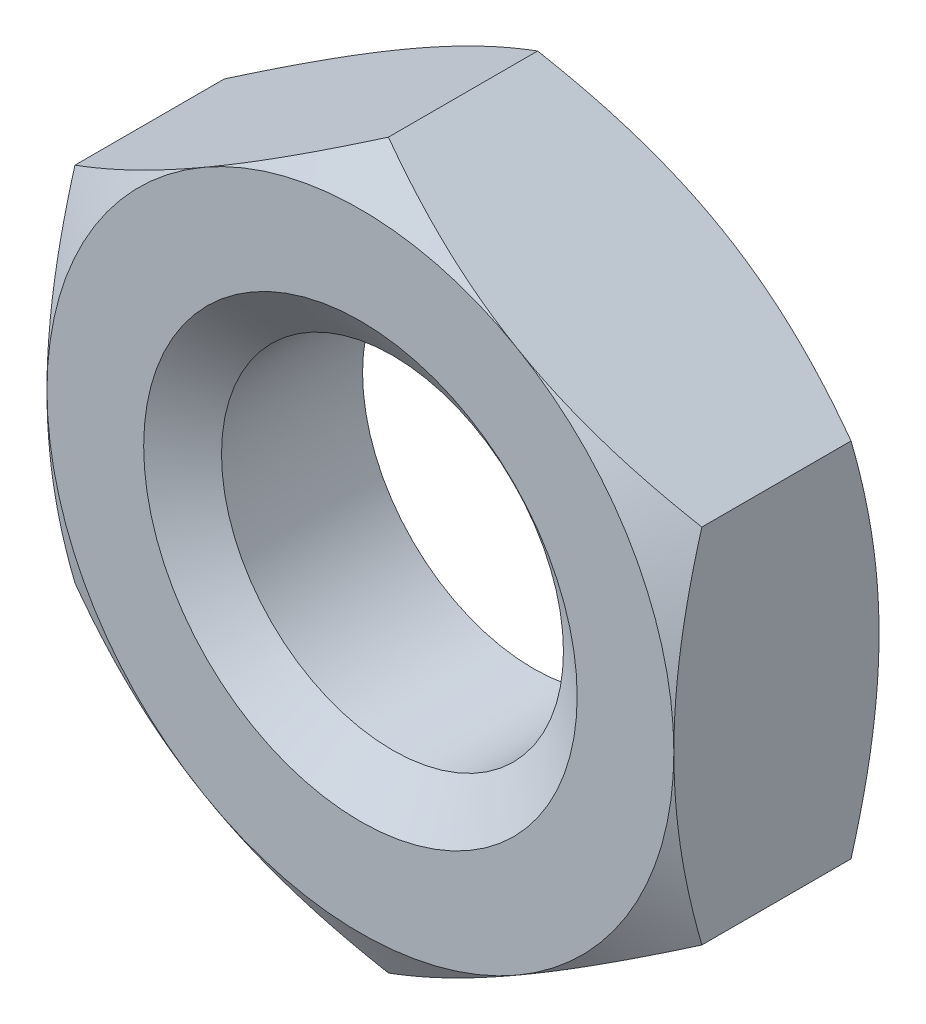
SolidWorks part; units mm, degrees
extrude "BaseNut" add sketch "BaseNutSke" against normal blind 1.8
sketch "BaseNutSke" plane through (0, 0, 0) normal (0, 0, 1) x (1, 0, 0)
  line L6 (2.75, 1.5877) -> (2.75, -1.5877)
  line L7 (-2.75, 1.5877) -> (-2.75, -1.5877)
  line L8 (2.75, 1.5877) -> (0, 3.1754)
  line L9 (0, 3.1754) -> (-2.75, 1.5877)
  line L10 (-2.75, -1.5877) -> (0, -3.1754)
  line L11 (0, -3.1754) -> (2.75, -1.5877)
  circle A0 centre (0, 0) radius 1.5
  point P8 (-2.75, 0)
  point P9 (0, 1.5)
  point P13 (0, 0)
  dimension "Tap_drill" = 3
  dimension "D1" = 120
  dimension "Width_flats" = 5.5
material "Alloy Steel"
ref_plane "Plane1" through (0, 0, 0) normal (0, 0, 1) x (1, 0, 0)
ref_plane "Plane2" through (0, 0, 0) normal (0, 1, 0) x (1, 0, 0)
ref_plane "Plane3" through (0, 0, 0) normal (1, 0, 0) x (0, 0, -1)
sketch "Sketch3" plane through (0, 0, 0) normal (1, 0, 0) x (0, 0, -1)
  line L0 (1.8, 2.75) -> (1.5544, 3.1754)
  line L1 (1.5544, 3.1754) -> (1.5544, 13.1754)
  line L2 (1.5544, 13.1754) -> (11.8, 13.1754)
  line L3 (11.8, 13.1754) -> (11.8, 2.75)
  line L4 (11.8, 2.75) -> (1.8, 2.75)
  line L5 (1.8, 1.5877) -> (1.8, 3.1754) construction
  line L6 (1.8, 3.1754) -> (0, 3.1754) construction
  line L7 (0, 0) -> (1.8, 0) construction
  line L8 (1.8, 0) -> (0, 0) construction
  line L9 (0.9, 3.1754) -> (0.9, 13.1754) construction
  line L10 (0.2456, 13.1754) -> (-10, 13.1754)
  line L11 (-10, 13.1754) -> (-10, 2.75)
  line L12 (-10, 2.75) -> (0, 2.75)
  line L13 (0, 2.75) -> (0.2456, 3.1754)
  line L14 (0.2456, 3.1754) -> (0.2456, 13.1754)
  line L15 (1.8, -1.5) -> (1.8, 1.5) construction
  line L16 (1.8, 3.1754) -> (0, 3.1754) construction
  dimension "D1" = 2.75
  dimension "D4" = 10
  dimension "D3" = 10
  dimension "D2" = 30
revolve "Double-Chamfer" cut sketch "Sketch3" angle 360 about L7
sketch "Sketch5" plane through (0, 0, 0) normal (1, 0, 0) x (0, 0, -1)
  line L0 (0, 1.9017) -> (0.2812, 1.5)
  line L1 (0.2812, 1.5) -> (0, 1.5)
  line L2 (0, 1.5) -> (0, 1.9017)
  line L3 (1.8, 1.9017) -> (1.8, 1.5)
  line L5 (1.8, 1.5) -> (1.5187, 1.5)
  line L6 (1.5187, 1.5) -> (1.8, 1.9017)
  line L7 (0, 1.5) -> (0, -1.5) construction
  line L8 (1.8, -1.5) -> (1.8, 1.5) construction
  line L9 (0, 0) -> (1.8, 0) construction
  dimension "D1" = 35
  dimension "D2" = 0.2812
revolve "EndChamfer" cut sketch "Sketch5" angle 360 about L9
equation "\"D1@Sketch3\" = \"Width_flats@BaseNutSke\" / 2"
equation "\"Mass\"= \"SW-질량\" / 1000"
equation "\"D2@Sketch5\"= \"Tap_drill@BaseNutSke\" * ( 0.15 / 1.6 )"
